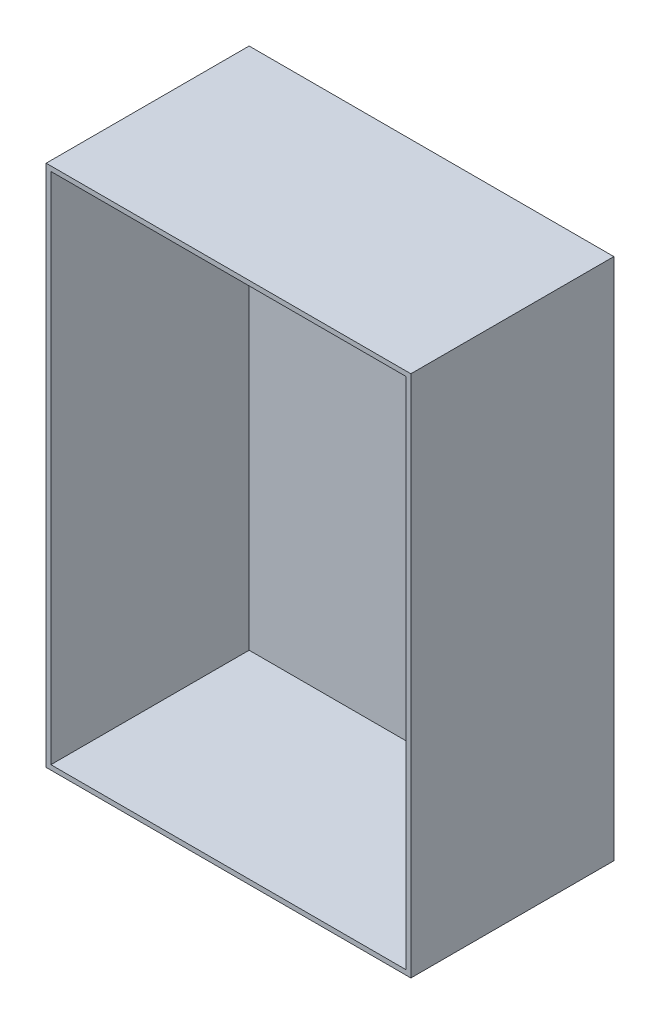
SolidWorks part; units mm, degrees
ref_plane "Front Plane" through (0, 0, 0) normal (0, 0, 1) x (1, 0, 0)
ref_plane "Top Plane" through (0, 0, 0) normal (0, 1, 0) x (1, 0, 0)
ref_plane "Right Plane" through (0, 0, 0) normal (1, 0, 0) x (0, 0, -1)
sketch "Sketch1" plane through (0, 0, 0) normal (0, 0, 1) x (1, 0, 0)
  line L1 (0, 0) -> (230, 0)
  line L2 (0, 0) -> (0, 330)
  line L3 (0, 330) -> (230, 330)
  line L4 (230, 0) -> (230, 330)
  line L5 (3, 3) -> (227, 3)
  line L6 (3, 3) -> (3, 327)
  line L7 (3, 327) -> (227, 327)
  line L8 (227, 3) -> (227, 327)
  dimension "D1" = 3
  dimension "D2" = 227
  dimension "D3" = 230
  dimension "D4" = 3
  dimension "D5" = 327
  dimension "D6" = 330
extrude "Profile" add sketch "Sketch1" along normal blind 128
sketch "Sketch2" plane through (0, 0, 0) normal (0, 0, 1) x (1, 0, 0)
  line L1 (3, 3) -> (227, 3)
  line L2 (3, 3) -> (3, 327)
  line L3 (3, 327) -> (227, 327)
  line L4 (227, 3) -> (227, 327)
extrude "Back" add sketch "Sketch2" along normal blind 3
equation "\"Profile_Depth\" = 128mm"
equation "\"D1@Profile\" = \"Profile_Depth\""
equation "\"Back_Depth\" = 3mm"
equation "\"D1@Back\" = \"Back_Depth\""
equation "\"EnvelopeWidth\" = 230mm"
equation "\"EnvelopeHeight\" = 330mm"
